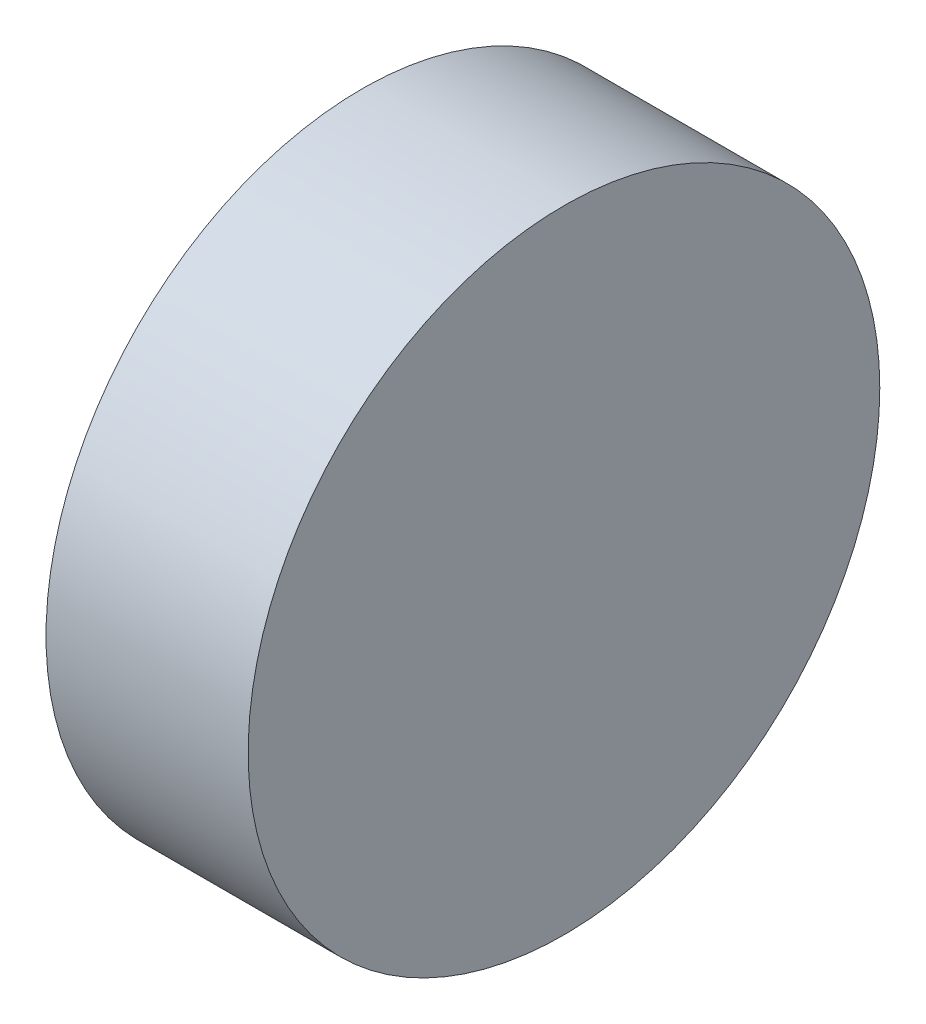
SolidWorks part; units mm, degrees
ref_plane "Front Plane" through (0, 0, 0) normal (0, 0, 1) x (1, 0, 0)
ref_plane "Top Plane" through (0, 0, 0) normal (0, 1, 0) x (1, 0, 0)
ref_plane "Right Plane" through (0, 0, 0) normal (1, 0, 0) x (0, 0, -1)
sketch "Sketch1" plane through (0, 0, 0) normal (1, 0, 0) x (0, 0, -1)
  circle A0 centre (0, 0) radius 317.5
  dimension "D1" = 635
extrude "Boss-Extrude1" add sketch "Sketch1" along normal blind 203.2
sketch "Sketch2" plane through (203.2, 0, 0) normal (1, 0, 0) x (0, 0, -1)
  line L0 (-317.5, 0) -> (317.5, 0) construction
  line L1 (0, -317.5) -> (0, 317.5)
  circle A0 centre (0, 0) radius 317.5 construction
  circle A1 centre (76.2, 0) radius 63.5
  dimension "D1" = 127
  dimension "D2" = 76.2
